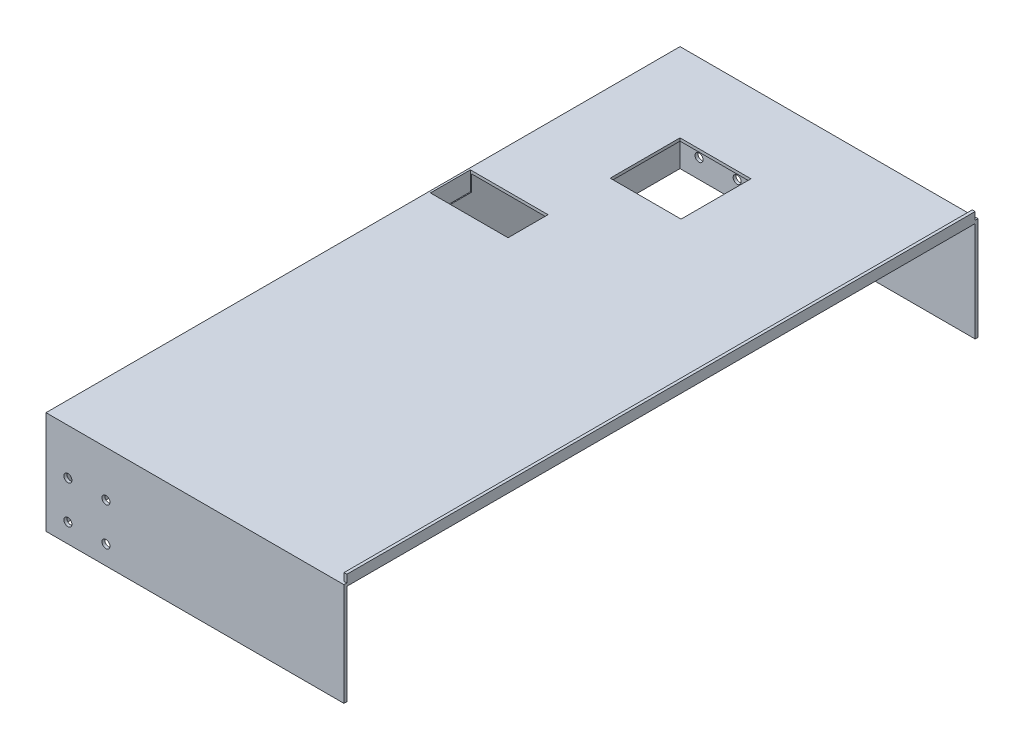
SolidWorks part; units mm, degrees
ref_plane "Front Plane" through (0, 0, 0) normal (0, 0, 1) x (1, 0, 0)
ref_plane "Top Plane" through (0, 0, 0) normal (0, 1, 0) x (1, 0, 0)
ref_plane "Right Plane" through (0, 0, 0) normal (1, 0, 0) x (0, 0, -1)
sketch "Sketch4" plane through (0, 0, 0) normal (0, 1, 0) x (1, 0, 0)
  line L0 (179.4784, 330) -> (334.4784, 330)
  line L1 (334.4784, 330) -> (334.4784, 0)
  line L2 (334.4784, 0) -> (179.4784, 0)
  line L3 (179.4784, 0) -> (179.4784, 200)
  line L7 (179.4784, 265) -> (179.4784, 330)
  line L8 (179.4784, 200) -> (179.4784, 265)
  dimension "D2" = 65
  dimension "D4" = 200
  dimension "D5" = 155
  dimension "D6" = 155
extrude "Boss-Extrude4" add sketch "Sketch4" along normal blind 1.5 separate body
sketch "Sketch5" plane through (0, 0, 0) normal (0, 0, 1) x (1, 0, 0)
  line L1 (179.4784, 1.5) -> (334.4784, 1.5)
  line L2 (179.4784, 1.5) -> (179.4784, -52.5)
  line L3 (179.4784, -52.5) -> (334.4784, -52.5)
  line L4 (334.4784, 1.5) -> (334.4784, -52.5)
  dimension "D1" = 54
sketch "Sketch7" plane through (0, 0, -330) normal (0, 0, -1) x (-1, 0, 0)
  line L1 (-179.4784, 1.5) -> (-334.4784, 1.5)
  line L2 (-179.4784, 1.5) -> (-179.4784, -52.5)
  line L3 (-179.4784, -52.5) -> (-334.4784, -52.5)
  line L4 (-334.4784, 1.5) -> (-334.4784, -52.5)
  dimension "D1" = 54
  dimension "D2" = 155
sketch "Sketch8" plane through (0, 1.5, 0) normal (0, 1, 0) x (1, 0, 0)
  line L0 (179.4784, 330) -> (334.4784, 330) construction
  line L1 (334.4784, 0) -> (332.9784, 0)
  line L2 (334.4784, 0) -> (334.4784, 330)
  line L3 (334.4784, 330) -> (332.9784, 330)
  line L4 (332.9784, 0) -> (332.9784, 330)
  dimension "D1" = 1.5
extrude "Boss-Extrude5" add sketch "Sketch5" along normal blind 1.5
extrude "Boss-Extrude14" add sketch "Sketch8" along normal blind 4
extrude "Boss-Extrude18" add sketch "Sketch7" along normal blind 1.5
sketch "Sketch9" plane through (179.4784, 0, 0) normal (-1, 0, 0) x (0, 0, 1)
  line L1 (-331.5, 1.5) -> (1.5, 1.5)
  line L2 (-331.5, 1.5) -> (-331.5, -52.5)
  line L3 (-331.5, -52.5) -> (1.5, -52.5)
  line L4 (1.5, 1.5) -> (1.5, -52.5)
extrude "Boss-Extrude19" add sketch "Sketch9" along normal blind 1.5
sketch "Sketch10" plane through (0, 0, -331.5) normal (0, 0, -1) x (-1, 0, 0)
  circle A0 centre (-209.4784, -42.5) radius 2.1
sketch "Sketch11" plane through (0, 0, -331.5) normal (0, 0, -1) x (-1, 0, 0)
  circle A0 centre (-189.4784, -42.5) radius 2.1
sketch "Sketch12" plane through (0, 0, -331.5) normal (0, 0, -1) x (-1, 0, 0)
  circle A0 centre (-189.4784, -22.5) radius 2.1
sketch "Sketch13" plane through (0, 0, -331.5) normal (0, 0, -1) x (-1, 0, 0)
  circle A0 centre (-209.4784, -22.5) radius 2.1
sketch "Sketch14" plane through (0, 0, 1.5) normal (0, 0, 1) x (1, 0, 0)
  circle A0 centre (189.4784, -22.5) radius 2.1
sketch "Sketch15" plane through (0, 0, 1.5) normal (0, 0, 1) x (1, 0, 0)
  circle A0 centre (209.4784, -22.5) radius 2.1
sketch "Sketch16" plane through (0, 0, 1.5) normal (0, 0, 1) x (1, 0, 0)
  circle A0 centre (189.4784, -42.5) radius 2.1
sketch "Sketch17" plane through (0, 0, 1.5) normal (0, 0, 1) x (1, 0, 0)
  circle A0 centre (209.4784, -42.5) radius 2.1
extrude "Cut-Extrude1" cut sketch "Sketch10" against normal blind 10
extrude "Cut-Extrude2" cut sketch "Sketch17" against normal blind 10
extrude "Cut-Extrude3" cut sketch "Sketch16" against normal blind 10
extrude "Cut-Extrude4" cut sketch "Sketch11" against normal blind 10
extrude "Cut-Extrude5" cut sketch "Sketch12" against normal blind 10
extrude "Cut-Extrude6" cut sketch "Sketch13" against normal blind 10
extrude "Cut-Extrude7" cut sketch "Sketch14" against normal blind 10
extrude "Cut-Extrude8" cut sketch "Sketch15" against normal blind 10
sketch "Sketch18" plane through (0, 1.5, 0) normal (0, 1, 0) x (1, 0, 0)
  line L1 (178.9875, 220.3848) -> (219.7642, 220.3848)
  line L2 (178.9875, 220.3848) -> (178.9875, 199.3811)
  line L3 (178.9875, 199.3811) -> (219.7642, 199.3811)
  line L4 (219.7642, 220.3848) -> (219.7642, 199.3811)
  point P4 (178.9875, 220.3848)
  point P6 (179.4784, 220.4006)
  point P7 (0, 0)
  point P8 (0, 0)
  point P9 (0, 0)
extrude "Cut-Extrude9" cut sketch "Sketch18" against normal blind 10
sketch "Sketch21" plane through (0, 1.5, 0) normal (0, 1, 0) x (1, 0, 0)
  line L1 (219.4784, 290) -> (256.7252, 290)
  line L2 (219.4784, 290) -> (219.4784, 253.3051)
  line L3 (219.4784, 253.3051) -> (256.7252, 253.3051)
  line L4 (256.7252, 290) -> (256.7252, 253.3051)
extrude "Cut-Extrude12" cut sketch "Sketch21" against normal blind 10
